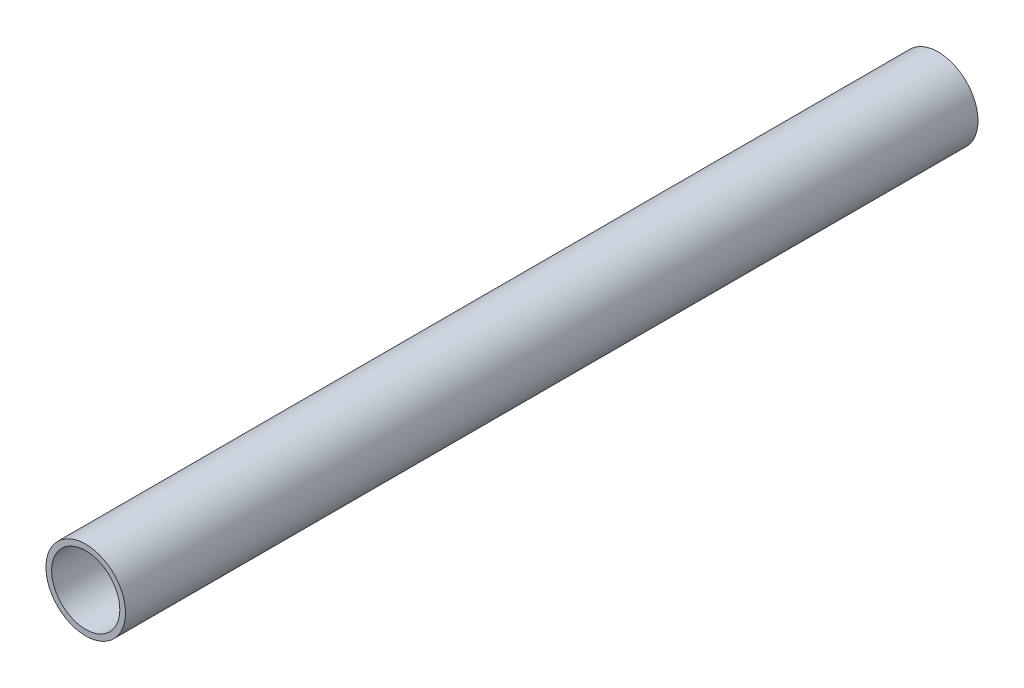
SolidWorks part; units mm, degrees
ref_plane "Спереди" through (0, 0, 0) normal (0, 0, 1) x (1, 0, 0)
ref_plane "Сверху" through (0, 0, 0) normal (0, 1, 0) x (1, 0, 0)
ref_plane "Справа" through (0, 0, 0) normal (1, 0, 0) x (0, 0, -1)
sketch "Эскиз1" plane through (0, 0, 0) normal (0, 0, 1) x (1, 0, 0)
  circle A0 centre (0, 0) radius 6
  circle A1 centre (0, 0) radius 7
  dimension "D2" = 12
  dimension "D1" = 1
extrude "Трубка алюминиевая 12мм" add sketch "Эскиз1" along normal blind 150
